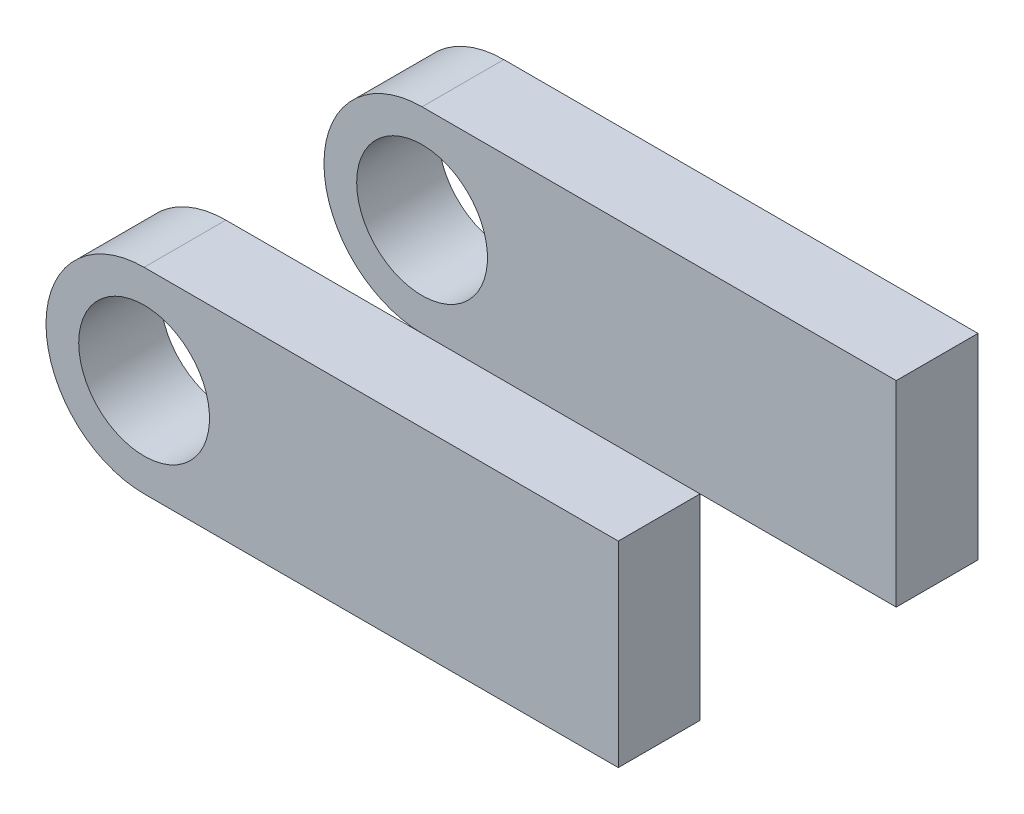
SolidWorks part; units mm, degrees
material "AISI 4130 Steel, normalized at 870C"
ref_plane "Front Plane" through (0, 0, 0) normal (0, 0, 1) x (1, 0, 0)
ref_plane "Top Plane" through (0, 0, 0) normal (0, 1, 0) x (1, 0, 0)
ref_plane "Right Plane" through (0, 0, 0) normal (1, 0, 0) x (0, 0, -1)
sketch "Sketch7" plane through (0, 0, 0) normal (0, 1, 0) x (1, 0, 0)
  line L0 (0, 6) -> (35, 6)
  line L1 (35, 6) -> (35, 11)
  line L2 (35, 11) -> (0, 11)
  line L4 (0, 11) -> (0, 6)
  line L5 (0, -11) -> (35, -11)
  line L6 (35, -11) -> (35, -6)
  line L7 (35, -6) -> (0, -6)
  line L8 (0, -6) -> (0, -11)
  line L9 (0, 6) -> (0, -6) construction
  point P2 (0, 0)
  dimension "D1" = 12
  dimension "D2" = 5
  dimension "D3" = 35
extrude "Boss-Extrude3" add sketch "Sketch7" along normal blind 12
sketch "Sketch8" plane through (0, 0, -11) normal (0, 0, -1) x (-1, 0, 0)
  line L1 (-35, 12) -> (0, 12) construction
  line L2 (-35, 0) -> (0, 0) construction
  line L3 (0, 12) -> (0, 0) construction
  line L6 (-6, 12) -> (6.2691, 12)
  line L7 (6.2691, 12) -> (6.2691, 0)
  line L8 (6.2691, 0) -> (-6, 0)
  arc A0 (-6, 12) -> (-6, 0) centre (-6, 6) cw
  point P9 (0, 6)
  point P12 (0, 6)
extrude "Cut-Extrude9" cut sketch "Sketch8" against normal blind 22
sketch "Sketch9" plane through (0, 0, -11) normal (0, 0, -1) x (-1, 0, 0)
  circle A0 centre (-6, 6) radius 4
  dimension "D1" = 8
extrude "Cut-Extrude10" cut sketch "Sketch9" against normal blind 22
